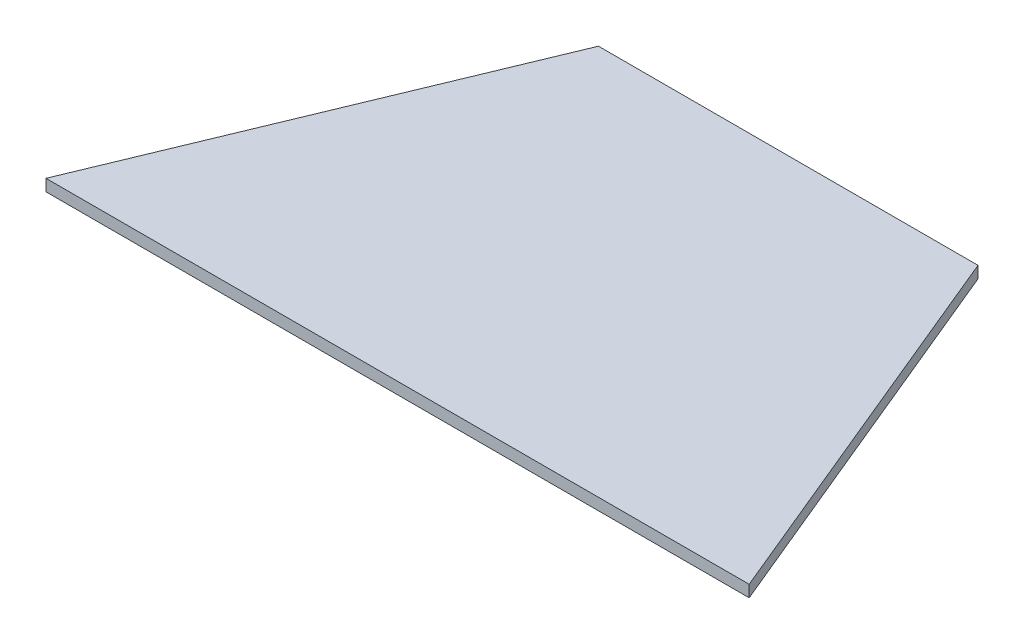
SolidWorks part; units mm, degrees
ref_plane "Front Plane" through (0, 0, 0) normal (0, 0, 1) x (1, 0, 0)
ref_plane "Top Plane" through (0, 0, 0) normal (0, 1, 0) x (1, 0, 0)
ref_plane "Right Plane" through (0, 0, 0) normal (1, 0, 0) x (0, 0, -1)
sketch "Sketch1" plane through (0, 0, 0) normal (0, 1, 0) x (1, 0, 0)
  line L0 (0, 0) -> (180, 0)
  line L3 (90, 0) -> (90, 100) construction
  line L5 (0, 0) -> (41.4214, 100)
  line L6 (180, 0) -> (138.5786, 100)
  line L7 (41.4214, 100) -> (138.5786, 100)
extrude "Boss-Extrude1" add sketch "Sketch1" along normal blind 3
